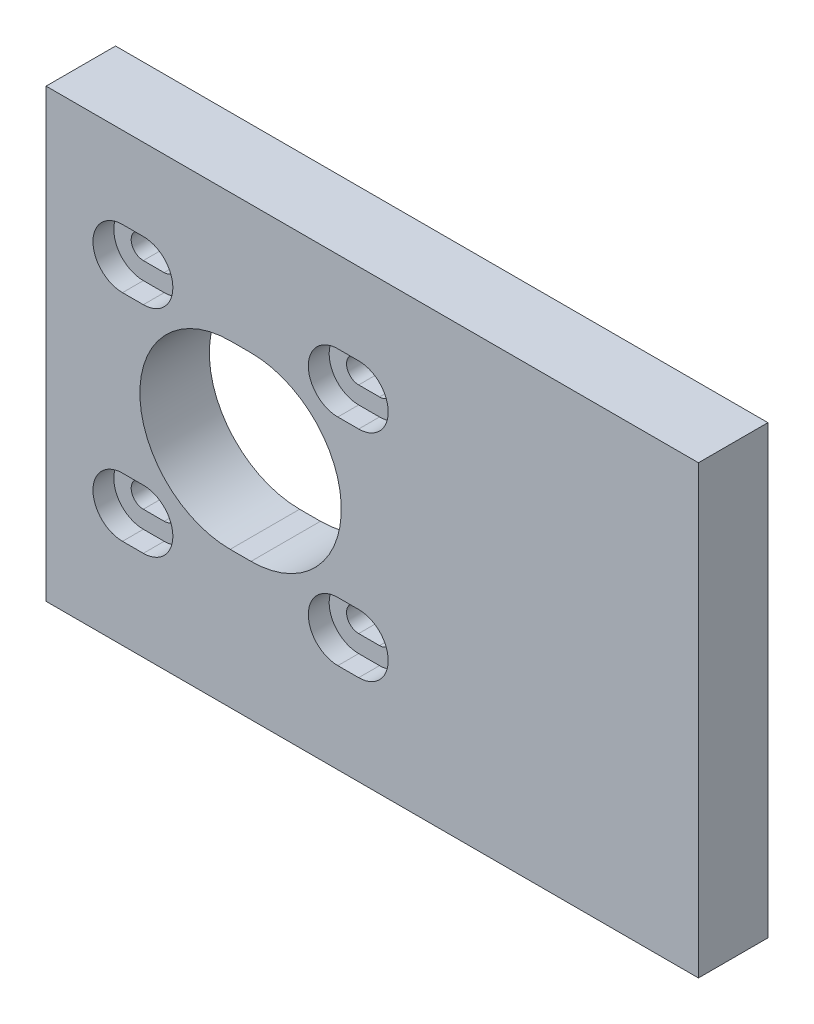
SolidWorks part; units mm, degrees
ref_plane "Front Plane" through (0, 0, 0) normal (0, 0, 1) x (1, 0, 0)
ref_plane "Top Plane" through (0, 0, 0) normal (0, 1, 0) x (1, 0, 0)
ref_plane "Right Plane" through (0, 0, 0) normal (1, 0, 0) x (0, 0, -1)
sketch "Sketch1" plane through (0, 0, 0) normal (0, 0, 1) x (1, 0, 0)
  line L1 (-50.949, 32.0052) -> (42.9629, 32.0052)
  line L2 (-50.949, 32.0052) -> (-50.949, -32.232)
  line L3 (-50.949, -32.232) -> (42.9629, -32.232)
  line L4 (42.9629, 32.0052) -> (42.9629, -32.232)
extrude "Boss-Extrude1" add sketch "Sketch1" along normal blind 10
sketch "Sketch2" plane through (0, 0, 10) normal (0, 0, 1) x (1, 0, 0)
  line L0 (-45.949, 22.0052) -> (-2.949, -20.9948) construction
  line L1 (-45.949, 22.0052) -> (-2.949, 22.0052) construction
  line L2 (-45.949, 22.0052) -> (-45.949, -20.9948) construction
  line L3 (-45.949, -20.9948) -> (-2.949, -20.9948) construction
  line L4 (-2.949, 22.0052) -> (-2.949, -20.9948) construction
  line L5 (-2.949, 22.0052) -> (-45.949, -20.9948) construction
  line L6 (-39.949, 16.0052) -> (-36.949, 16.0052) construction
  line L7 (-39.949, 17.7552) -> (-36.949, 17.7552)
  line L8 (-39.949, 14.2552) -> (-36.949, 14.2552)
  line L9 (-8.949, 16.0052) -> (-5.949, 16.0052) construction
  line L10 (-8.949, 17.7552) -> (-5.949, 17.7552)
  line L11 (-8.949, 14.2552) -> (-5.949, 14.2552)
  line L12 (-8.949, -14.9948) -> (-5.949, -14.9948) construction
  line L13 (-8.949, -13.2448) -> (-5.949, -13.2448)
  line L14 (-8.949, -16.7448) -> (-5.949, -16.7448)
  line L15 (-39.949, -14.9948) -> (-36.949, -14.9948) construction
  line L16 (-39.949, -13.2448) -> (-36.949, -13.2448)
  line L17 (-39.949, -16.7448) -> (-36.949, -16.7448)
  line L18 (-24.449, 0.5052) -> (-21.449, 0.5052) construction
  line L19 (-24.449, 13.5052) -> (-21.449, 13.5052)
  line L20 (-24.449, -12.4948) -> (-21.449, -12.4948)
  line L21 (42.9629, 32.0052) -> (-50.949, 32.0052) construction
  line L22 (-50.949, 32.0052) -> (-50.949, -32.232) construction
  arc A0 (-39.949, 17.7552) -> (-39.949, 14.2552) centre (-39.949, 16.0052) ccw
  arc A1 (-36.949, 14.2552) -> (-36.949, 17.7552) centre (-36.949, 16.0052) ccw
  arc A2 (-8.949, 17.7552) -> (-8.949, 14.2552) centre (-8.949, 16.0052) ccw
  arc A3 (-5.949, 14.2552) -> (-5.949, 17.7552) centre (-5.949, 16.0052) ccw
  arc A4 (-8.949, -13.2448) -> (-8.949, -16.7448) centre (-8.949, -14.9948) ccw
  arc A5 (-5.949, -16.7448) -> (-5.949, -13.2448) centre (-5.949, -14.9948) ccw
  arc A6 (-39.949, -13.2448) -> (-39.949, -16.7448) centre (-39.949, -14.9948) ccw
  arc A7 (-36.949, -16.7448) -> (-36.949, -13.2448) centre (-36.949, -14.9948) ccw
  arc A8 (-24.449, 13.5052) -> (-24.449, -12.4948) centre (-24.449, 0.5052) ccw
  arc A9 (-21.449, -12.4948) -> (-21.449, 13.5052) centre (-21.449, 0.5052) ccw
  point P6 (-38.449, 16.0052)
  point P11 (-7.449, 16.0052)
  point P18 (-7.449, -14.9948)
  point P25 (-38.449, -14.9948)
  point P34 (-22.949, 0.5052)
  dimension "D2" = 1.75
  dimension "D4" = 13
  dimension "D1" = 3
  dimension "D3" = 3
  dimension "D5" = 31
  dimension "D6" = 43
  dimension "D7" = 10
  dimension "D8" = 5
extrude "Cut-Extrude1" cut sketch "Sketch2" against normal blind 20
sketch "Sketch3" plane through (0, 0, 10) normal (0, 0, 1) x (1, 0, 0)
  line L0 (-36.949, 17.7552) -> (-39.949, 17.7552) construction
  line L1 (-39.949, 14.2552) -> (-36.949, 14.2552) construction
  line L2 (-5.949, 17.7552) -> (-8.949, 17.7552) construction
  line L3 (-8.949, 14.2552) -> (-5.949, 14.2552) construction
  line L4 (-5.949, -13.2448) -> (-8.949, -13.2448) construction
  line L5 (-8.949, -16.7448) -> (-5.949, -16.7448) construction
  line L6 (-39.949, -16.7448) -> (-36.949, -16.7448) construction
  line L7 (-36.949, -13.2448) -> (-39.949, -13.2448) construction
  line L8 (-36.949, 17.7552) -> (-39.949, 17.7552) construction
  line L9 (-39.949, 14.2552) -> (-36.949, 14.2552) construction
  line L10 (-5.949, 17.7552) -> (-8.949, 17.7552) construction
  line L11 (-8.949, 14.2552) -> (-5.949, 14.2552) construction
  line L12 (-5.949, -13.2448) -> (-8.949, -13.2448) construction
  line L13 (-8.949, -16.7448) -> (-5.949, -16.7448) construction
  line L14 (-39.949, -16.7448) -> (-36.949, -16.7448) construction
  line L15 (-36.949, -13.2448) -> (-39.949, -13.2448) construction
  line L16 (-36.949, 20.2552) -> (-39.949, 20.2552)
  line L17 (-39.949, 11.7552) -> (-36.949, 11.7552)
  line L18 (-5.949, 20.2552) -> (-8.949, 20.2552)
  line L19 (-8.949, 11.7552) -> (-5.949, 11.7552)
  line L20 (-5.949, -10.7448) -> (-8.949, -10.7448)
  line L21 (-8.949, -19.2448) -> (-5.949, -19.2448)
  line L22 (-39.949, -19.2448) -> (-36.949, -19.2448)
  line L23 (-36.949, -10.7448) -> (-39.949, -10.7448)
  arc A0 (-39.949, 17.7552) -> (-39.949, 14.2552) centre (-39.949, 16.0052) ccw construction
  arc A1 (-36.949, 14.2552) -> (-36.949, 17.7552) centre (-36.949, 16.0052) ccw construction
  arc A2 (-8.949, 17.7552) -> (-8.949, 14.2552) centre (-8.949, 16.0052) ccw construction
  arc A3 (-5.949, 14.2552) -> (-5.949, 17.7552) centre (-5.949, 16.0052) ccw construction
  arc A4 (-5.949, -16.7448) -> (-5.949, -13.2448) centre (-5.949, -14.9948) ccw construction
  arc A5 (-8.949, -13.2448) -> (-8.949, -16.7448) centre (-8.949, -14.9948) ccw construction
  arc A6 (-36.949, -16.7448) -> (-36.949, -13.2448) centre (-36.949, -14.9948) ccw construction
  arc A7 (-39.949, -13.2448) -> (-39.949, -16.7448) centre (-39.949, -14.9948) ccw construction
  arc A8 (-39.949, 17.7552) -> (-39.949, 14.2552) centre (-39.949, 16.0052) ccw construction
  arc A9 (-36.949, 14.2552) -> (-36.949, 17.7552) centre (-36.949, 16.0052) ccw construction
  arc A10 (-8.949, 17.7552) -> (-8.949, 14.2552) centre (-8.949, 16.0052) ccw construction
  arc A11 (-5.949, 14.2552) -> (-5.949, 17.7552) centre (-5.949, 16.0052) ccw construction
  arc A12 (-5.949, -16.7448) -> (-5.949, -13.2448) centre (-5.949, -14.9948) ccw construction
  arc A13 (-8.949, -13.2448) -> (-8.949, -16.7448) centre (-8.949, -14.9948) ccw construction
  arc A14 (-36.949, -16.7448) -> (-36.949, -13.2448) centre (-36.949, -14.9948) ccw construction
  arc A15 (-39.949, -13.2448) -> (-39.949, -16.7448) centre (-39.949, -14.9948) ccw construction
  arc A16 (-39.949, 20.2552) -> (-39.949, 11.7552) centre (-39.949, 16.0052) ccw
  arc A17 (-36.949, 11.7552) -> (-36.949, 20.2552) centre (-36.949, 16.0052) ccw
  arc A18 (-8.949, 20.2552) -> (-8.949, 11.7552) centre (-8.949, 16.0052) ccw
  arc A19 (-5.949, 11.7552) -> (-5.949, 20.2552) centre (-5.949, 16.0052) ccw
  arc A20 (-8.949, -10.7448) -> (-8.949, -19.2448) centre (-8.949, -14.9948) ccw
  arc A21 (-5.949, -19.2448) -> (-5.949, -10.7448) centre (-5.949, -14.9948) ccw
  arc A22 (-36.949, -19.2448) -> (-36.949, -10.7448) centre (-36.949, -14.9948) ccw
  arc A23 (-39.949, -10.7448) -> (-39.949, -19.2448) centre (-39.949, -14.9948) ccw
  dimension "D1" = 4.25
extrude "Cut-Extrude2" cut sketch "Sketch3" against normal blind 3
